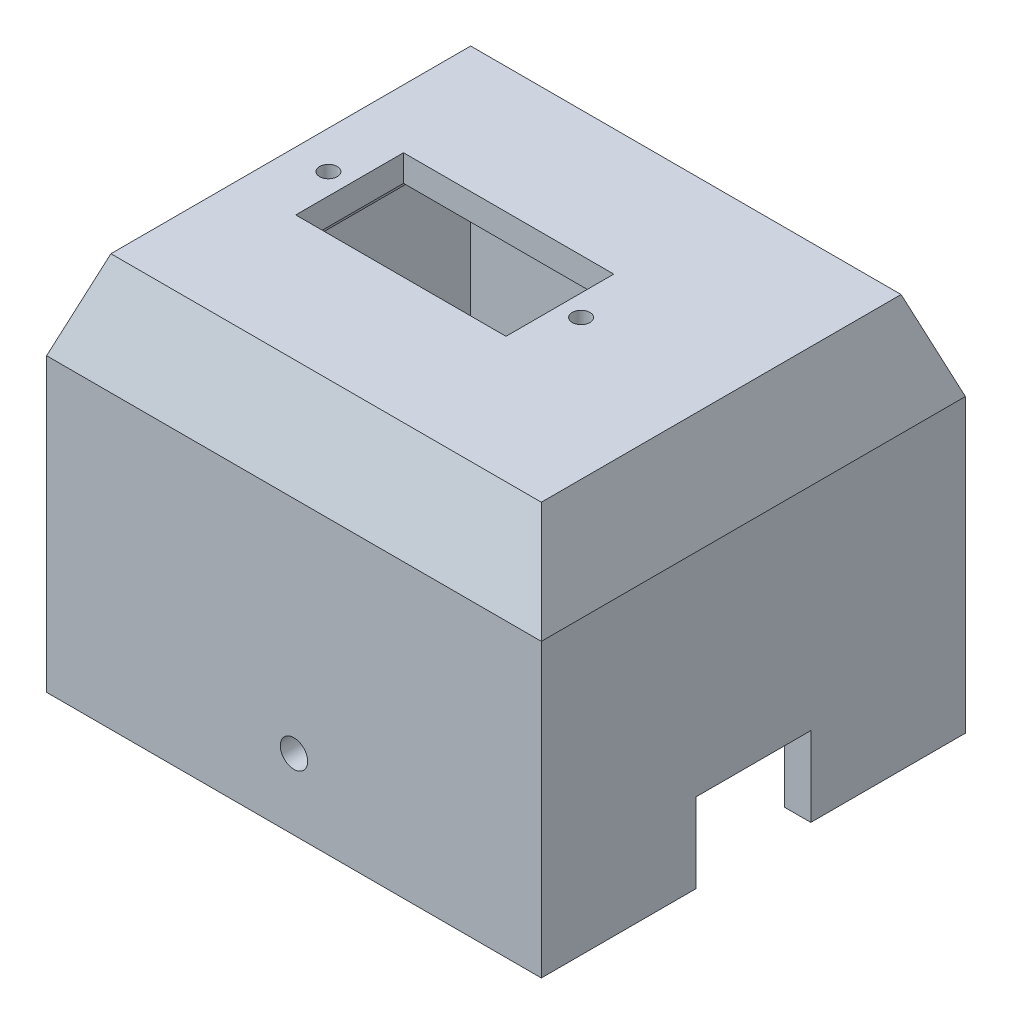
SolidWorks part; units mm, degrees
ref_plane "前视基准面" through (0, 0, 0) normal (0, 0, 1) x (1, 0, 0)
ref_plane "上视基准面" through (0, 0, 0) normal (0, 1, 0) x (1, 0, 0)
ref_plane "右视基准面" through (0, 0, 0) normal (1, 0, 0) x (0, 0, -1)
sketch "草图47" plane through (0, 0, 0) normal (0, 1, 0) x (1, 0, 0)
  line L1 (28, -24) -> (-28, -24)
  line L2 (28, -24) -> (28, 24)
  line L3 (28, 24) -> (-28, 24)
  line L4 (-28, -24) -> (-28, 24)
  line L5 (28, -24) -> (-28, 24) construction
  line L6 (28, 24) -> (-28, -24) construction
  point P0 (0, 0)
  dimension "D1" = 48
  dimension "D2" = 56
extrude "凸台-拉伸4" add sketch "草图47" along normal blind 43
chamfer "倒角1" distance 10 angle 20 4 edges at (0, 43, -24) (28, 43, 0) (0, 43, 24) (-28, 43, 0)
shell "抽壳1" thickness 3
sketch "草图48" plane through (0, 43, -43) normal (0, -1, 0) x (1, 0, 0)
  line L0 (-5.8, 47.679) -> (-5.8, 60.2141) construction
  line L1 (6.1, 36.9) -> (-17.7, 36.9)
  line L2 (6.1, 36.9) -> (6.1, 49.1)
  line L3 (6.1, 49.1) -> (-17.7, 49.1)
  line L4 (-17.7, 36.9) -> (-17.7, 49.1)
  line L5 (6.1, 36.9) -> (-17.7, 49.1) construction
  line L6 (6.1, 49.1) -> (-17.7, 36.9) construction
  line L13 (-20.1, 43) -> (-5.8, 43) construction
  circle A0 centre (-20.1, 43) radius 1
  circle A2 centre (8.5, 43) radius 1
  circle A3 centre (0, 43) radius 6.1 construction
  point P0 (-5.8, 43)
  point P6 (-5.8, 43)
  point P10 (0, 43)
  dimension "D4" = 2
  dimension "D1" = 23.8
  dimension "D2" = 12.2
  dimension "D3" = 14.3
extrude "切除-拉伸3" cut sketch "草图48" along normal up to next
sketch "草图49" plane through (0, 0, -24) normal (0, 0, -1) x (-1, 0, 0)
  line L0 (-28, 0) -> (28, 0) construction
  circle A0 centre (0, 8) radius 1.55
  point P4 (0, 0)
  dimension "D1" = 3.1
  dimension "D2" = 8
extrude "切除-拉伸4" cut sketch "草图49" against normal through all
sketch "草图50" plane through (28, 0, 0) normal (1, 0, 0) x (0, 0, -1)
  line L0 (-24, 0) -> (24, 0) construction
  line L1 (6.5, 9) -> (-6.5, 9)
  line L2 (6.5, 9) -> (6.5, 0)
  line L3 (6.5, 0) -> (-6.5, 0)
  line L4 (-6.5, 9) -> (-6.5, 0)
  line L5 (6.5, 9) -> (-6.5, 0) construction
  line L6 (6.5, 0) -> (-6.5, 9) construction
  point P0 (0, 4.5)
  dimension "D1" = 9
  dimension "D2" = 13
extrude "切除-拉伸5" cut sketch "草图50" against normal up to next
sketch "草图51" plane through (-28, 0, 0) normal (-1, 0, 0) x (0, 0, 1)
  line L0 (-24, 0) -> (24, 0) construction
  line L1 (5.3596, 21.8798) -> (-5.3596, 21.8798)
  line L2 (5.3596, 21.8798) -> (5.3596, 0)
  line L3 (5.3596, 0) -> (-5.3596, 0)
  line L4 (-5.3596, 21.8798) -> (-5.3596, 0)
  line L5 (5.3596, 21.8798) -> (-5.3596, 0) construction
  line L6 (5.3596, 0) -> (-5.3596, 21.8798) construction
  point P0 (0, 10.9399)
  point P7 (-6.2286, 21.8798)
  point P8 (0, 0)
extrude "切除-拉伸6" cut sketch "草图51" against normal up to next
